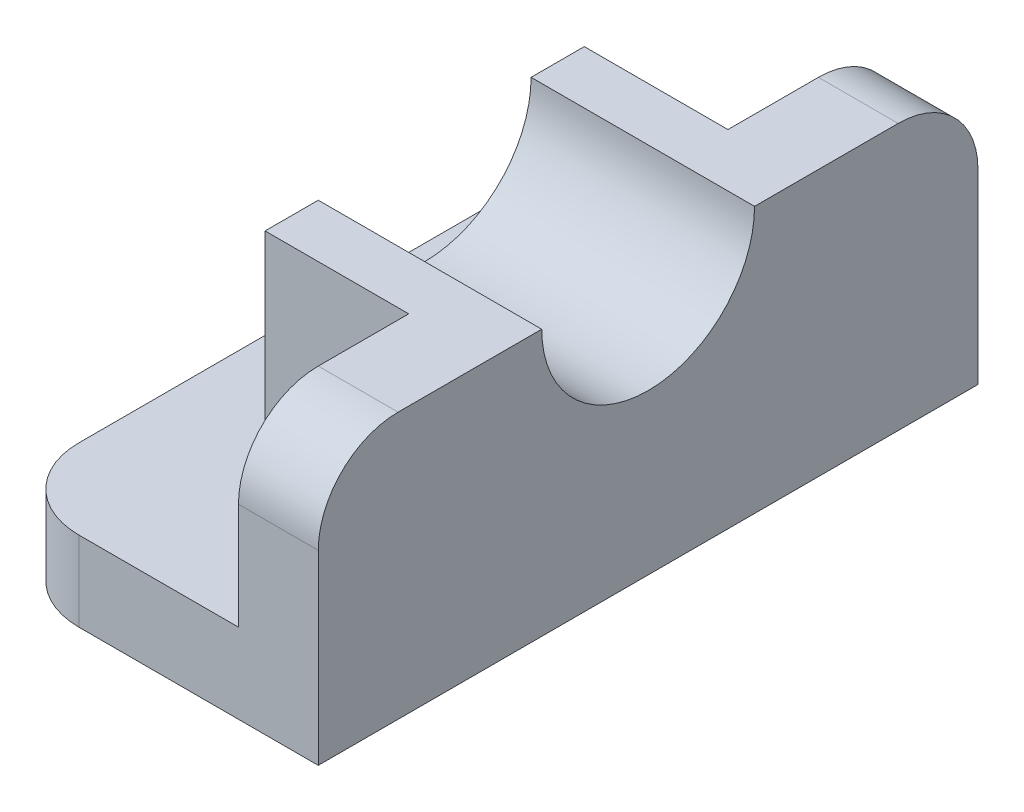
SolidWorks part; units mm, degrees
ref_plane "Front Plane" through (0, 0, 0) normal (0, 0, 1) x (1, 0, 0)
ref_plane "Top Plane" through (0, 0, 0) normal (0, 1, 0) x (1, 0, 0)
ref_plane "Right Plane" through (0, 0, 0) normal (1, 0, 0) x (0, 0, -1)
sketch "Sketch2" plane through (0, 0, 0) normal (0, 0, 1) x (1, 0, 0)
  line L0 (0, 0) -> (60, 0)
  line L1 (60, 0) -> (60, 50)
  line L2 (60, 50) -> (45, 50)
  line L3 (45, 50) -> (45, 15)
  line L4 (0, 0) -> (0, 15)
  line L5 (0, 15) -> (45, 15)
  dimension "D1" = 50
  dimension "D2" = 15
  dimension "D3" = 15
  dimension "D4" = 60
extrude "Boss-Extrude1" add sketch "Sketch2" along normal blind 124
fillet "Fillet1" radius 15 4 edges at (52.5, 50, 124) (0, 7.5, 124) (0, 7.5, 0) (52.5, 50, 0)
sketch "Sketch4" plane through (45, 0, 0) normal (-1, 0, 0) x (0, 0, 1)
  line L0 (109, 50) -> (15, 50) construction
  line L1 (32, 50) -> (92, 50)
  line L2 (32, 50) -> (32, 15)
  line L3 (32, 15) -> (92, 15)
  line L4 (92, 50) -> (92, 15)
  line L5 (124, 15) -> (0, 15) construction
  line L6 (124, 35) -> (124, 15) construction
  dimension "D1" = 60
  dimension "D2" = 32
extrude "Boss-Extrude2" add sketch "Sketch4" along normal blind 27
sketch "Sketch5" plane through (18, 0, 0) normal (-1, 0, 0) x (0, 0, 1)
  line L0 (92, 50) -> (32, 50) construction
  circle A0 centre (62, 50) radius 20
extrude "Cut-Extrude1" cut sketch "Sketch5" against normal blind 61
